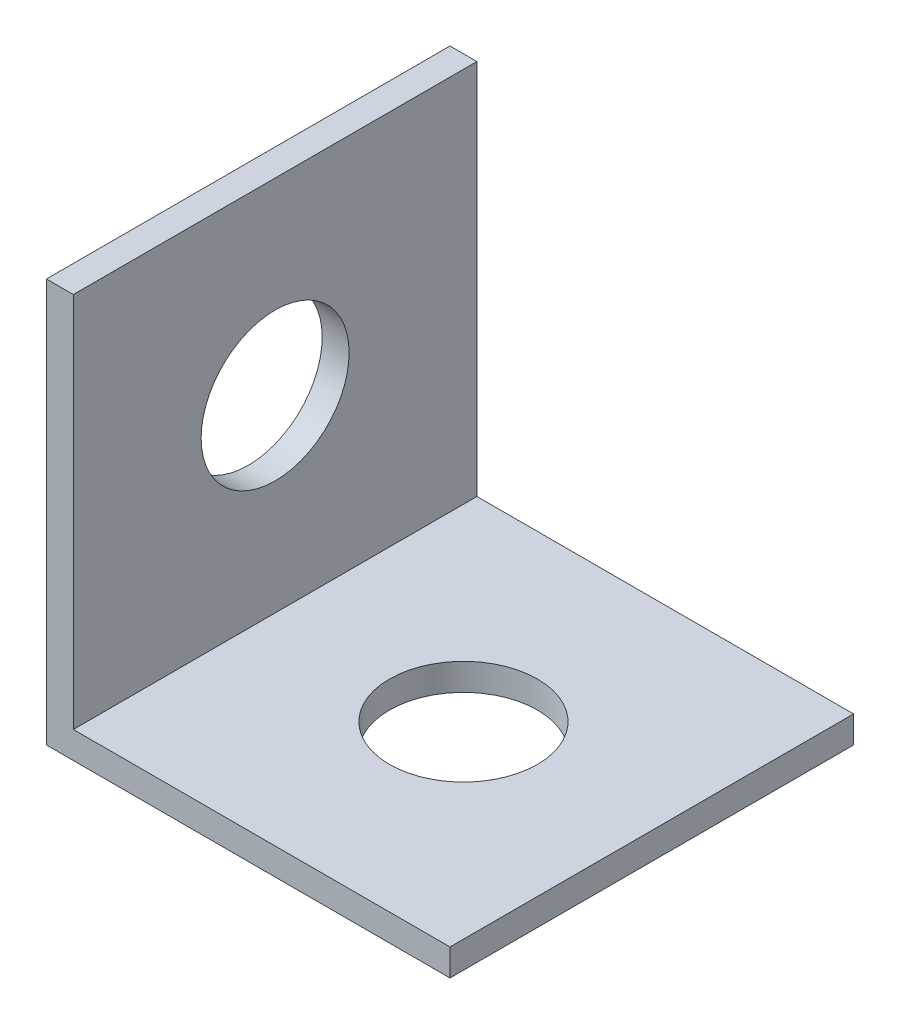
SolidWorks part; units mm, degrees
ref_plane "Front Plane" through (0, 0, 0) normal (0, 0, 1) x (1, 0, 0)
ref_plane "Top Plane" through (0, 0, 0) normal (0, 1, 0) x (1, 0, 0)
ref_plane "Right Plane" through (0, 0, 0) normal (1, 0, 0) x (0, 0, -1)
sketch "Sketch1" plane through (0, 0, 0) normal (0, 0, 1) x (1, 0, 0)
  line L0 (0, 0) -> (0, 15)
  line L1 (0, 15) -> (1, 15)
  line L2 (1, 15) -> (1, 1)
  line L3 (1, 1) -> (15, 1)
  line L4 (15, 1) -> (15, 0)
  line L5 (15, 0) -> (0, 0)
  point P3 (1.5, 1.5)
  dimension "D1" = 1
  dimension "D2" = 15
extrude "Boss-Extrude1" add sketch "Sketch1" along normal blind 15
sketch "Sketch2" plane through (0, 0, 0) normal (0, -1, 0) x (-1, 0, 0)
  line L0 (-8, 0) -> (-8, -15) construction
  line L1 (-15, 0) -> (-1, 0) construction
  line L2 (-15, -15) -> (-1, -15) construction
  line L3 (-8, -15) -> (-1, -7.5) construction
  line L4 (-1, -15) -> (-1, 0) construction
  line L5 (-1, -7.5) -> (-15, -7.5) construction
  line L6 (-15, -15) -> (-15, 0) construction
  circle A0 centre (-8, -7.5) radius 2.75
  dimension "D1" = 5.5
extrude "Cut-Extrude1" cut sketch "Sketch2" against normal blind 19.05
sketch "Sketch3" plane through (1, 0, 0) normal (1, 0, 0) x (0, 0, -1)
  line L0 (-15, 8) -> (0, 8) construction
  line L1 (-15, 1) -> (-15, 15) construction
  line L2 (0, 1) -> (0, 15) construction
  line L3 (0, 8) -> (-7.5, 15) construction
  line L4 (-15, 15) -> (0, 15) construction
  line L5 (-7.5, 15) -> (-7.5, 1) construction
  line L6 (-15, 1) -> (0, 1) construction
  circle A0 centre (-7.5, 8) radius 2.75
  dimension "D1" = 5.5
extrude "Cut-Extrude2" cut sketch "Sketch3" against normal through all
